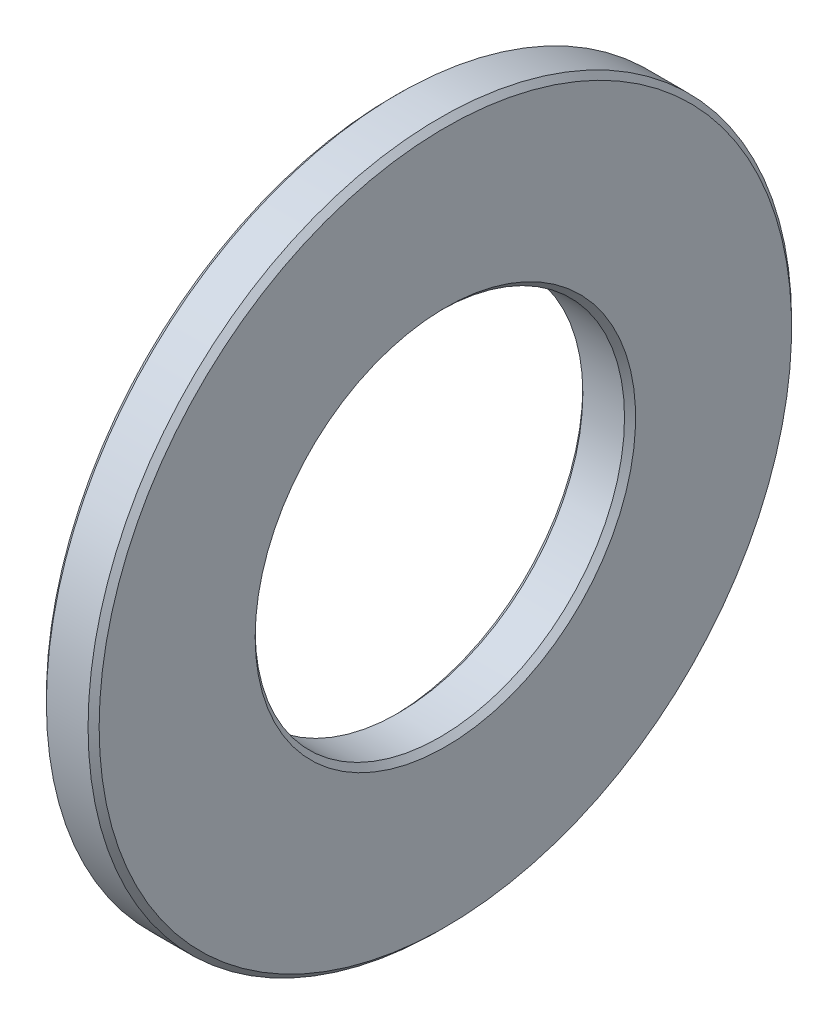
SolidWorks part; units mm, degrees
material "Phosphor bronze 10% D, UNS C52400"
ref_plane "Front Plane" through (0, 0, 0) normal (0, 0, 1) x (1, 0, 0)
ref_plane "Top Plane" through (0, 0, 0) normal (0, 1, 0) x (1, 0, 0)
ref_plane "Right Plane" through (0, 0, 0) normal (1, 0, 0) x (0, 0, -1)
sketch "Sketch1" plane through (0, 0, 0) normal (0, 0, 1) x (1, 0, 0)
  line L0 (0, 8.3344) -> (2.3813, 8.3344)
  line L3 (2.3813, 8.3344) -> (2.3812, 15.875)
  line L4 (2.3812, 15.875) -> (0, 15.875)
  line L5 (0, 15.875) -> (0, 8.3344)
  line L6 (0, 0) -> (44.8454, 0) construction
  dimension "D1" = 16.6687
  dimension "D2" = 2.3813
  dimension "D3" = 31.75
revolve "Revolve1" add sketch "Sketch1" angle 360 about L6
chamfer "Chamfer1" distance 0.25 angle 45 4 edges at (0, 0, 8.3344) (2.3812, 0, 15.875) (0, 0, 15.875) (2.3813, 0, 8.3344)
